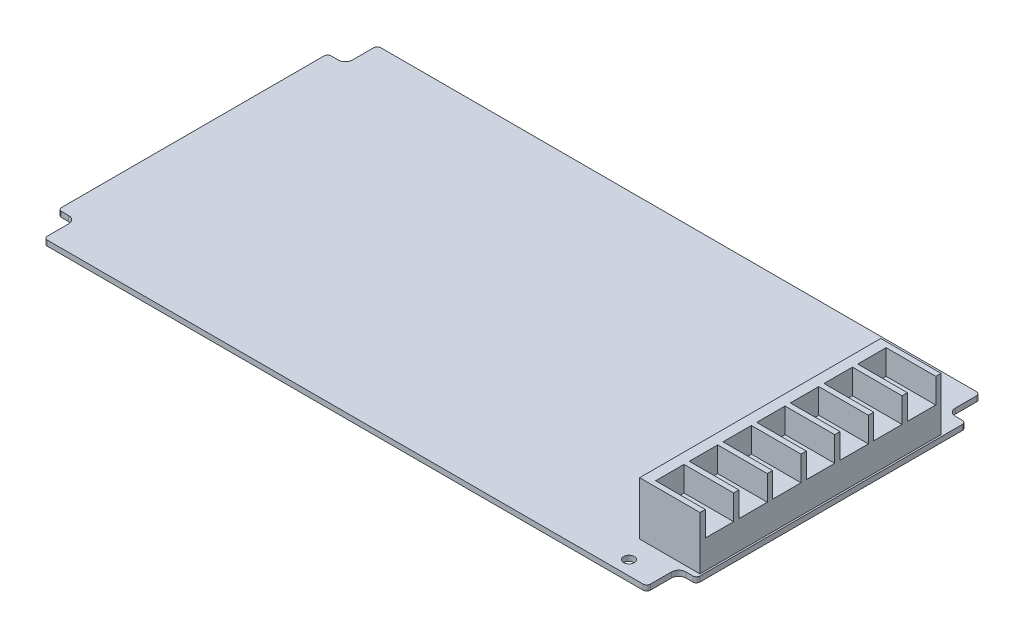
SolidWorks part; units mm, degrees
ref_plane "前视基准面" through (0, 0, 0) normal (0, 0, 1) x (1, 0, 0)
ref_plane "上视基准面" through (0, 0, 0) normal (0, 1, 0) x (1, 0, 0)
ref_plane "右视基准面" through (0, 0, 0) normal (1, 0, 0) x (0, 0, -1)
sketch "草图2" plane through (0, 0, 0) normal (0, 1, 0) x (1, 0, 0)
  line L1 (-90, -47) -> (90, -47)
  line L2 (-90, -47) -> (-90, 47)
  line L3 (-90, 47) -> (90, 47)
  line L4 (90, -47) -> (90, 47)
  line L5 (-90, -47) -> (90, 47) construction
  line L6 (-90, 47) -> (90, -47) construction
  point P0 (0, 0)
  dimension "D1" = 180
  dimension "D2" = 94
extrude "凸台-拉伸1" add sketch "草图2" along normal blind 1.5
sketch "草图3" plane through (0, 1.5, 0) normal (0, 1, 0) x (1, 0, 0)
  line L0 (85, 47) -> (85, 40)
  line L1 (90, 47) -> (-90, 47) construction
  line L2 (87, 38) -> (90, 38)
  line L3 (90, -47) -> (90, 47) construction
  line L4 (-54.3189, 0) -> (54.3189, 0) construction
  line L5 (0, -40.1048) -> (0, 40.1048) construction
  line L6 (85, 47) -> (90, 47)
  line L7 (90, 47) -> (90, 38)
  line L8 (87, -38) -> (90, -38)
  line L9 (85, -47) -> (90, -47)
  line L10 (85, -47) -> (85, -40)
  line L11 (90, -47) -> (90, -38)
  line L12 (-90, -47) -> (-90, -38)
  line L13 (-85, -47) -> (-85, -40)
  line L14 (-85, -47) -> (-90, -47)
  line L15 (-87, -38) -> (-90, -38)
  line L16 (-90, 47) -> (-90, 38)
  line L17 (-85, 47) -> (-90, 47)
  line L18 (-87, 38) -> (-90, 38)
  line L19 (-85, 47) -> (-85, 40)
  arc A0 (87, 38) -> (85, 40) centre (87, 40) cw
  arc A1 (87, -38) -> (85, -40) centre (87, -40) ccw
  arc A2 (-87, -38) -> (-85, -40) centre (-87, -40) cw
  arc A3 (-87, 38) -> (-85, 40) centre (-87, 40) ccw
  point P9 (85, 38)
  point P15 (0, 0)
  point P18 (0, 0)
  point P41 (-85, 38)
  dimension "D3" = 2
  dimension "D1" = 9
  dimension "D2" = 5
extrude "切除-拉伸1" cut sketch "草图3" against normal blind 1.5
fillet "圆角1" radius 1 8 edges at (-90, 0.75, -38) (-85, 0.75, -47) (-90, 0.75, 38) (-85, 0.75, 47) (85, 0.75, 47) (90, 0.75, 38) (85, 0.75, -47) (90, 0.75, -38)
sketch "草图4" plane through (0, 1.5, 0) normal (0, 1, 0) x (1, 0, 0)
  line L0 (-84, -47) -> (84, -47) construction
  line L1 (72.5, 31.5) -> (89.5, 31.5)
  line L2 (72.5, 31.5) -> (72.5, -36.5)
  line L3 (72.5, -36.5) -> (89.5, -36.5)
  line L4 (89.5, 31.5) -> (89.5, -36.5)
  line L6 (90, -37) -> (90, 37) construction
  dimension "D1" = 68
  dimension "D2" = 17
  dimension "D3" = 10.5
  dimension "D4" = 0.5
extrude "凸台-拉伸2" add sketch "草图4" along normal blind 15
sketch "草图6" plane through (0, 16.5, 0) normal (0, 1, 0) x (1, 0, 0)
  line L0 (89.5, -36.5) -> (89.5, 31.5) construction
  line L1 (75.5, 30) -> (89.5, 30)
  line L2 (75.5, 30) -> (75.5, 22)
  line L3 (75.5, 22) -> (89.5, 22)
  line L4 (89.5, 30) -> (89.5, 22)
  line L5 (72.5, 31.5) -> (72.5, -36.5) construction
  line L6 (89.5, 31.5) -> (72.5, 31.5) construction
  line L7 (75.5, 12.5) -> (89.5, 12.5)
  line L8 (75.5, 20.5) -> (75.5, 12.5)
  line L9 (75.5, 20.5) -> (89.5, 20.5)
  line L10 (89.5, 20.5) -> (89.5, 12.5)
  line L11 (75.5, 3) -> (89.5, 3)
  line L12 (75.5, 11) -> (75.5, 3)
  line L13 (75.5, 11) -> (89.5, 11)
  line L14 (89.5, 11) -> (89.5, 3)
  line L15 (75.5, -6.5) -> (89.5, -6.5)
  line L16 (75.5, 1.5) -> (75.5, -6.5)
  line L17 (75.5, 1.5) -> (89.5, 1.5)
  line L18 (89.5, 1.5) -> (89.5, -6.5)
  line L19 (75.5, -16) -> (89.5, -16)
  line L20 (75.5, -8) -> (75.5, -16)
  line L21 (75.5, -8) -> (89.5, -8)
  line L22 (89.5, -8) -> (89.5, -16)
  line L23 (75.5, -25.5) -> (89.5, -25.5)
  line L24 (75.5, -17.5) -> (75.5, -25.5)
  line L25 (75.5, -17.5) -> (89.5, -17.5)
  line L26 (89.5, -17.5) -> (89.5, -25.5)
  line L27 (75.5, -35) -> (89.5, -35)
  line L28 (75.5, -27) -> (75.5, -35)
  line L29 (75.5, -27) -> (89.5, -27)
  line L30 (89.5, -27) -> (89.5, -35)
  dimension "D1" = 3
  dimension "D2" = 1.5
  dimension "D3" = 8
  dimension "D4" = 7
extrude "切除-拉伸3" cut sketch "草图6" against normal blind 7
sketch "草图7" plane through (0, 9.5, 0) normal (0, 1, 0) x (1, 0, 0)
  line L0 (75.5, 26) -> (87.2085, 26) construction
  line L1 (75.5, 30) -> (75.5, 22) construction
  line L2 (82.5, 30) -> (82.5, 24.9397) construction
  line L3 (89.5, 30) -> (75.5, 30) construction
  circle A0 centre (82.5, 26) radius 1.5
  circle A1 centre (82.5, 16.5) radius 1.5
  circle A2 centre (82.5, 7) radius 1.5
  circle A3 centre (82.5, -2.5) radius 1.5
  circle A4 centre (82.5, -12) radius 1.5
  circle A5 centre (82.5, -21.5) radius 1.5
  circle A6 centre (82.5, -31) radius 1.5
  dimension "D1" = 3
  dimension "D2" = 7
extrude "切除-拉伸4" cut sketch "草图7" against normal up to surface (8 mm away) up to face at (0, 1.5, 0)
sketch "草图5" plane through (0, 1.5, 0) normal (0, 1, 0) x (1, 0, 0)
  line L0 (90, -37) -> (90, 37) construction
  line L1 (-84, -47) -> (84, -47) construction
  circle A0 centre (76, -43) radius 1.5
  dimension "D1" = 3
  dimension "D2" = 14
  dimension "D3" = 4
extrude "切除-拉伸2" cut sketch "草图5" against normal through all
